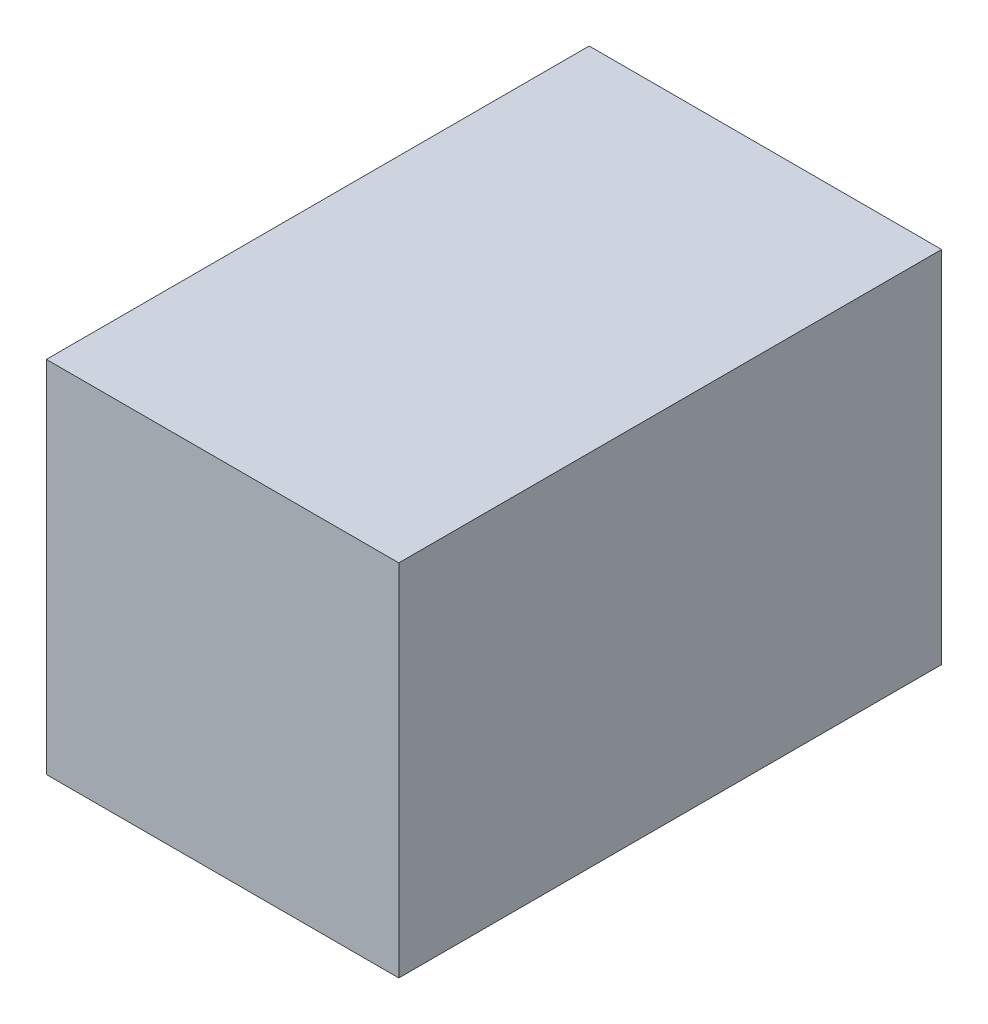
SolidWorks part; units mm, degrees
ref_plane "Front Plane" through (0, 0, 0) normal (0, 0, 1) x (1, 0, 0)
ref_plane "Top Plane" through (0, 0, 0) normal (0, 1, 0) x (1, 0, 0)
ref_plane "Right Plane" through (0, 0, 0) normal (1, 0, 0) x (0, 0, -1)
sketch "Sketch1" plane through (0, 0, 0) normal (0, 0, 1) x (1, 0, 0)
  line L4 (-17.4, -2.75) -> (17.4, -2.75)
  line L5 (17.4, -2.75) -> (17.4, 32.75)
  line L6 (17.4, 32.75) -> (-17.4, 32.75)
  line L7 (-17.4, 32.75) -> (-17.4, -2.75)
  line L8 (-17.4, -2.75) -> (17.4, -2.75)
  line L9 (17.4, -2.75) -> (17.4, 32.75)
  line L10 (17.4, 32.75) -> (-17.4, 32.75)
  line L11 (-17.4, 32.75) -> (-17.4, -2.75)
  dimension "D1" = 0
extrude "Boss-Extrude1" add sketch "Sketch1" against normal up to surface (53.6 mm away)
